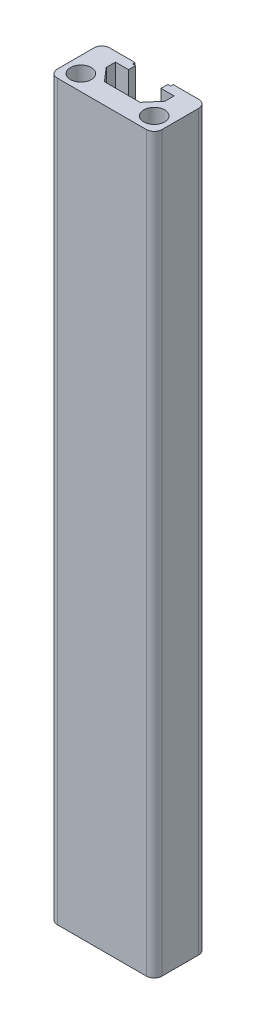
SolidWorks part; units mm, degrees
ref_plane "前视基准面" through (0, 0, 0) normal (0, 0, 1) x (1, 0, 0)
ref_plane "上视基准面" through (0, 0, 0) normal (0, 1, 0) x (1, 0, 0)
ref_plane "右视基准面" through (0, 0, 0) normal (1, 0, 0) x (0, 0, -1)
sketch "草图1" plane through (0, 0, 0) normal (0, 1, 0) x (1, 0, 0)
  line L0 (0, 0) -> (20, 0)
  line L1 (20, 0) -> (20, 10)
  line L2 (20, 10) -> (13.65, 10)
  line L3 (0, 10) -> (0, 0)
  line L4 (6.35, 10) -> (6.35, 9.5104)
  line L5 (6.35, 9.5104) -> (6.9, 9.5104)
  line L6 (6.9, 9.5104) -> (6.9, 8.2)
  line L7 (6.9, 8.2) -> (4.4, 8.2)
  line L8 (4.4, 8.2) -> (4.4, 6.4475)
  line L9 (4.4, 6.4475) -> (6.5873, 3.9)
  line L11 (15.6, 6.4475) -> (15.6, 8.2)
  line L12 (15.6, 8.2) -> (13.1, 8.2)
  line L13 (13.1, 8.2) -> (13.1, 9.5104)
  line L14 (13.1, 9.5104) -> (13.65, 9.5104)
  line L15 (13.65, 9.5104) -> (13.65, 10)
  line L16 (6.35, 10) -> (0, 10)
  line L17 (10, 0) -> (10, 13.7687) construction
  line L18 (6.5873, 3.9) -> (13.4127, 3.9)
  line L19 (13.4127, 3.9) -> (15.6, 6.4475)
  circle A0 centre (3, 3) radius 2
  circle A1 centre (17, 3) radius 2
  point P12 (10, 3.9)
  dimension "D8" = 4
  dimension "D1" = 20
  dimension "D2" = 10
  dimension "D3" = 7.3
  dimension "D4" = 6.2
  dimension "D5" = 1.8
  dimension "D6" = 4.3
  dimension "D7" = 11.2
  dimension "D9" = 3
  dimension "D10" = 14
extrude "凸台-拉伸1" add sketch "草图1" along normal blind 140
fillet "圆角1" radius 1.5 4 edges at (0, 70, -10) (0, 70, 0) (20, 70, -10) (20, 70, 0)
